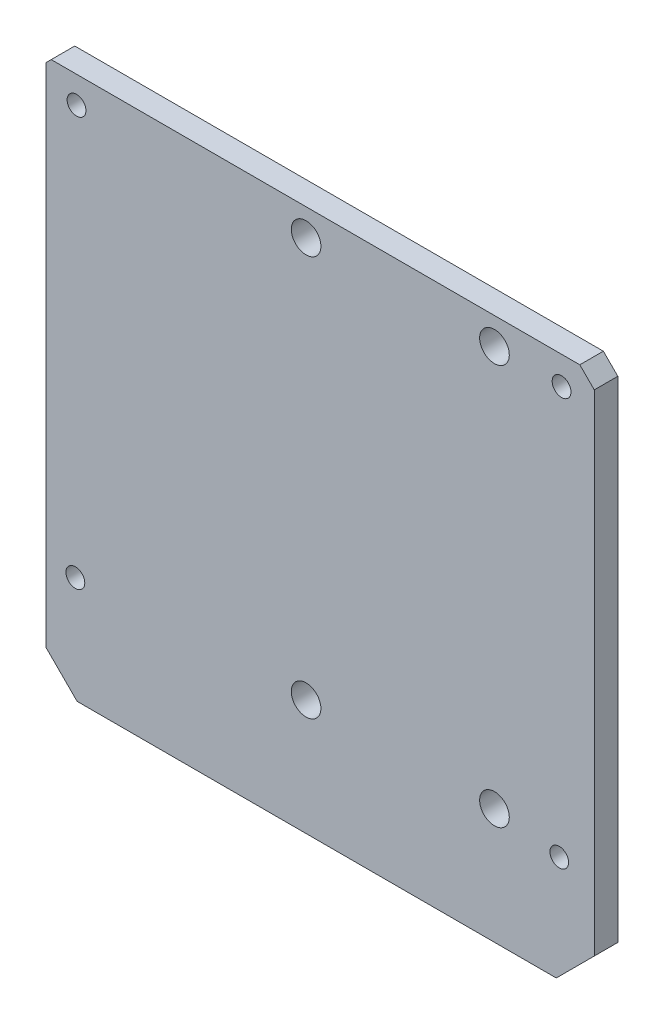
SolidWorks part; units mm, degrees
ref_plane "Front Plane" through (0, 0, 0) normal (0, 0, 1) x (1, 0, 0)
ref_plane "Top Plane" through (0, 0, 0) normal (0, 1, 0) x (1, 0, 0)
ref_plane "Right Plane" through (0, 0, 0) normal (1, 0, 0) x (0, 0, -1)
other "Graphic1"
other "Graphic (Open) -1"
sketch "Sketch1" plane through (0, 0, 0) normal (0, 0, 1) x (1, 0, 0)
  line L0 (4033.1001, -3054.5071) -> (4035.2402, -3052.3501)
  line L1 (4035.2402, -3052.3501) -> (4259.7515, -3052.3501)
  line L2 (4259.7515, -3052.3501) -> (4265.8999, -3058.4985)
  line L3 (4265.8999, -3058.4985) -> (4265.8999, -3266.7515)
  line L4 (4265.8999, -3266.7515) -> (4249.7515, -3282.8999)
  line L5 (4249.7515, -3282.8999) -> (4046.2485, -3282.8999)
  line L6 (4046.2485, -3282.8999) -> (4033.1001, -3269.7515)
  line L7 (4033.1001, -3269.7515) -> (4033.1001, -3054.5071)
  circle A0 centre (4046, -3063.7501) radius 4
  circle A1 centre (4143.4964, -3063.7701) radius 6.2953
  circle A2 centre (4223.5, -3063.75) radius 6.2988
  circle A3 centre (4252.0001, -3064.25) radius 4
  circle A4 centre (4251.0213, -3237.7954) radius 3.9623
  circle A5 centre (4223.5, -3233.7504) radius 6.2986
  circle A6 centre (4143.493, -3233.7587) radius 6.2893
  circle A7 centre (4045.5, -3237.75) radius 4
extrude "Boss-Extrude1" add sketch "Sketch1" along normal blind 10
scale "Scale1" bodies to scale 145 scale about centroid uniform scaling yes scale factor 0.25431
